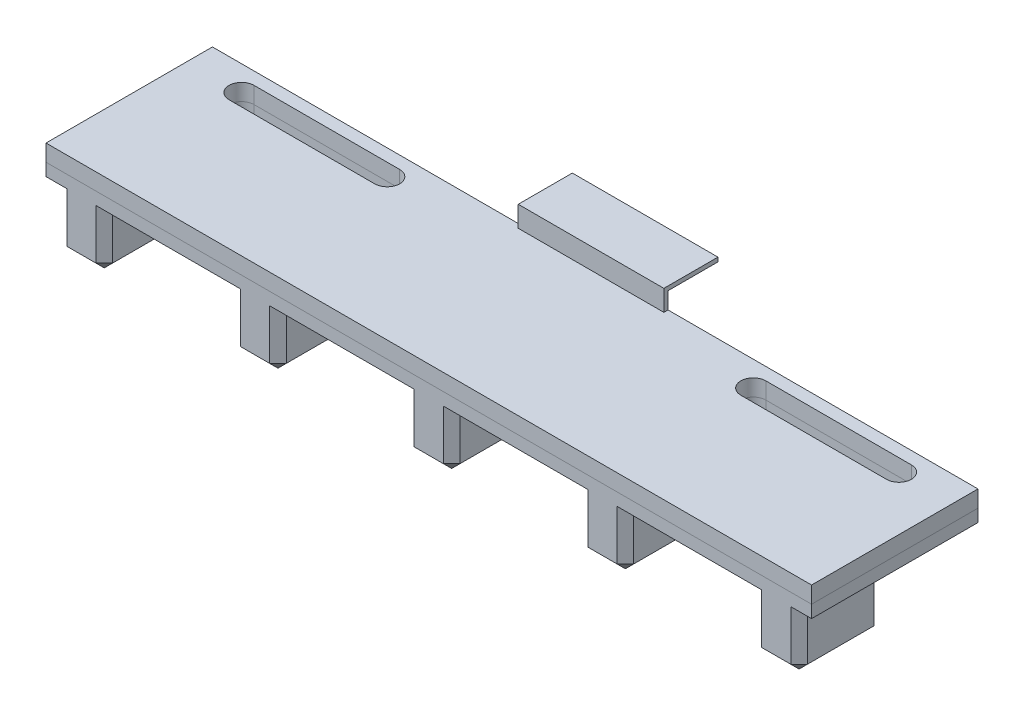
SolidWorks part; units mm, degrees
ref_plane "前视基准面" through (0, 0, 0) normal (0, 0, 1) x (1, 0, 0)
ref_plane "上视基准面" through (0, 0, 0) normal (0, 1, 0) x (1, 0, 0)
ref_plane "右视基准面" through (0, 0, 0) normal (1, 0, 0) x (0, 0, -1)
sketch "草图1" plane through (0, 0, 0) normal (0, 1, 0) x (1, 0, 0)
  line L1 (-46, -10) -> (46, -10)
  line L2 (-46, -10) -> (-46, 10)
  line L3 (-46, 10) -> (46, 10)
  line L4 (46, -10) -> (46, 10)
  line L5 (-46, -10) -> (46, 10) construction
  line L6 (-46, 10) -> (46, -10) construction
  point P0 (0, 0)
  dimension "D1" = 92
  dimension "D2" = 20
extrude "凸台-拉伸1" add sketch "草图1" along normal blind 1.5
sketch "草图2" plane through (0, 0, 0) normal (0, -1, 0) x (1, 0, 0)
  line L0 (-46, 10) -> (46, 10) construction
  line L1 (-44.5, 10) -> (-39, 10)
  line L2 (-44.5, 10) -> (-44.5, 0)
  line L3 (-44.5, 0) -> (-39, 0)
  line L4 (-39, 10) -> (-39, 0)
  line L5 (-46, -10) -> (-46, 10) construction
  dimension "D1" = 5.5
  dimension "D2" = 10
  dimension "D3" = 1.5
extrude "凸台-拉伸2" add sketch "草图2" along normal blind 7
chamfer "倒角1" distance 1 angle 45 8 edges at (-39, -7, 5) (-39, -3.5, 0) (-44.5, -3.5, 0) (-41.75, -7, 0) (-44.5, -7, 5) (-39, -3.5, 10) (-41.75, -7, 10) (-44.5, -3.5, 10)
pattern_linear "阵列(线性)2" count 5 spacing 20.875 along (1, 0, 0) of "凸台-拉伸2", "倒角1"
sketch "草图4" plane through (0, 0, 0) normal (1, 0, 0) x (0, 0, -1)
  line L0 (9.5, 1.5) -> (9.5, 6)
  line L1 (-10, 1.5) -> (10, 1.5) construction
  line L2 (9.5, 6) -> (16, 6)
  line L3 (16, 6) -> (16, 5.5)
  line L4 (16, 5.5) -> (10, 5.5)
  line L5 (10, 5.5) -> (10, 1.5)
  line L6 (10, 1.5) -> (9.5, 1.5)
  line L7 (10, 1.5) -> (10, 0) construction
  dimension "D1" = 0.5
  dimension "D2" = 4.5
  dimension "D3" = 6
extrude "凸台-拉伸3" add sketch "草图4" along normal mid plane 17.5
sketch "草图5" plane through (0, 1.5, 0) normal (0, 1, 0) x (1, 0, 0)
  line L0 (-39.5, 7) -> (-22, 7) construction
  line L1 (-39.5, 8.5) -> (-22, 8.5)
  line L2 (-39.5, 5.5) -> (-22, 5.5)
  line L3 (0, 0) -> (0, -10) construction
  line L4 (-46, -10) -> (46, -10) construction
  line L5 (39.5, 7) -> (22, 7) construction
  line L6 (39.5, 8.5) -> (22, 8.5)
  line L7 (39.5, 5.5) -> (22, 5.5)
  line L10 (-46, 10) -> (-46, -10) construction
  line L11 (-8.75, 10) -> (-46, 10) construction
  arc A0 (-39.5, 8.5) -> (-39.5, 5.5) centre (-39.5, 7) ccw
  arc A1 (-22, 5.5) -> (-22, 8.5) centre (-22, 7) ccw
  arc A2 (39.5, 8.5) -> (39.5, 5.5) centre (39.5, 7) cw
  arc A3 (22, 5.5) -> (22, 8.5) centre (22, 7) cw
  point P2 (-30.75, 7)
  point P14 (30.75, 7)
  dimension "D2" = 1.5
  dimension "D3" = 5
  dimension "D1" = 17.5
  dimension "D4" = 3
extrude "切除-拉伸1" cut sketch "草图5" against normal up to surface (1.5 mm away) up to face at (0, 0, 4.5455)
sketch "草图6" plane through (0, 1.5, 0) normal (0, 1, 0) x (1, 0, 0)
  line L0 (39.5, 8.5) -> (22, 8.5) construction
  line L1 (22, 5.5) -> (39.5, 5.5) construction
  line L2 (-39.5, 5.5) -> (-22, 5.5) construction
  line L3 (-22, 8.5) -> (-39.5, 8.5) construction
  line L4 (39.5, 8.5) -> (22, 8.5)
  line L5 (22, 5.5) -> (39.5, 5.5)
  line L6 (-39.5, 5.5) -> (-22, 5.5)
  line L7 (-22, 8.5) -> (-39.5, 8.5)
  line L8 (8.75, 9.5) -> (-8.75, 9.5)
  line L9 (-8.75, 9.5) -> (-8.75, 10)
  line L10 (-8.75, 10) -> (-46, 10)
  line L11 (-46, 10) -> (-46, -10)
  line L12 (-46, -10) -> (46, -10)
  line L13 (46, -10) -> (46, 10)
  line L14 (46, 10) -> (8.75, 10)
  line L15 (8.75, 10) -> (8.75, 9.5)
  line L16 (8.75, 9.5) -> (-8.75, 9.5)
  line L17 (-8.75, 9.5) -> (-8.75, 10)
  line L18 (-8.75, 10) -> (-46, 10)
  line L19 (-46, 10) -> (-46, -10)
  line L20 (-46, -10) -> (46, -10)
  line L21 (46, -10) -> (46, 10)
  line L22 (46, 10) -> (8.75, 10)
  line L23 (8.75, 10) -> (8.75, 9.5)
  arc A0 (39.5, 5.5) -> (39.5, 8.5) centre (39.5, 7) ccw construction
  arc A1 (22, 8.5) -> (22, 5.5) centre (22, 7) ccw construction
  arc A2 (-22, 5.5) -> (-22, 8.5) centre (-22, 7) ccw construction
  arc A3 (-39.5, 8.5) -> (-39.5, 5.5) centre (-39.5, 7) ccw construction
  arc A4 (39.5, 5.5) -> (39.5, 8.5) centre (39.5, 7) ccw
  arc A5 (22, 8.5) -> (22, 5.5) centre (22, 7) ccw
  arc A6 (-22, 5.5) -> (-22, 8.5) centre (-22, 7) ccw
  arc A7 (-39.5, 8.5) -> (-39.5, 5.5) centre (-39.5, 7) ccw
  dimension "D1" = 0
extrude "凸台-拉伸4" add sketch "草图6" along normal blind 2 separate body
